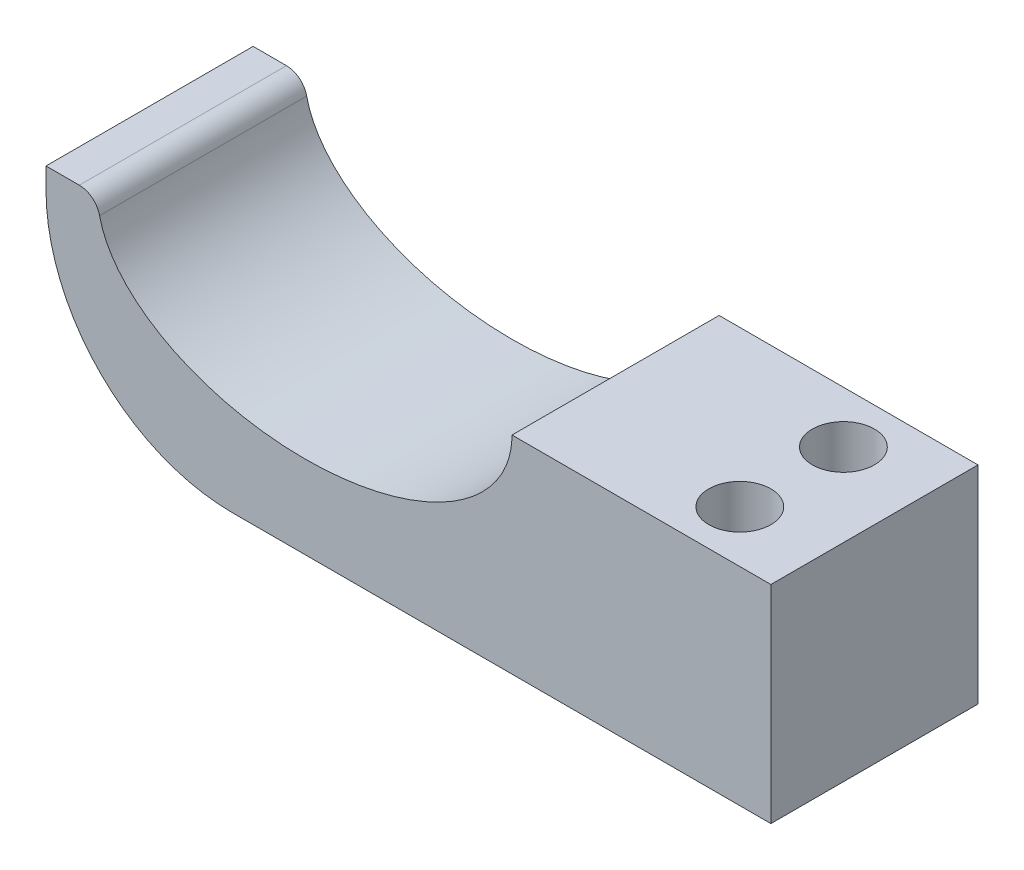
SolidWorks part; units mm, degrees
ref_plane "Front Plane" through (0, 0, 0) normal (0, 0, 1) x (1, 0, 0)
ref_plane "Top Plane" through (0, 0, 0) normal (0, 1, 0) x (1, 0, 0)
ref_plane "Right Plane" through (0, 0, 0) normal (1, 0, 0) x (0, 0, -1)
sketch "Sketch1" plane through (0, 0, 0) normal (0, 1, 0) x (1, 0, 0)
  line L1 (-44.45, 12.7) -> (44.45, 12.7)
  line L2 (-44.45, 12.7) -> (-44.45, -12.7)
  line L3 (-44.45, -12.7) -> (44.45, -12.7)
  line L4 (44.45, 12.7) -> (44.45, -12.7)
  line L5 (-44.45, 12.7) -> (44.45, -12.7) construction
  line L6 (-44.45, -12.7) -> (44.45, 12.7) construction
  point P1 (0, 0)
  dimension "D1" = 88.9
  dimension "D2" = 25.4
extrude "Boss-Extrude1" add sketch "Sketch1" along normal blind 25.4
sketch "Sketch2" plane through (0, 0, 12.7) normal (0, 0, 1) x (1, 0, 0)
  line L0 (-44.45, 25.4) -> (44.45, 25.4) construction
  ellipse E0 centre (-12.7, 25.4) end of major axis (-38.1, 25.4) minor radius 15.24
  dimension "D1" = 6.35
  dimension "D2" = 15.24
  dimension "D3" = 50.8
extrude "Cut-Extrude1" cut sketch "Sketch2" against normal through all
fillet "Fillet1" radius 2.54 1 edges at (-38.1, 25.4, 0)
sketch "Sketch5" plane through (0, 25.4, 0) normal (0, 1, 0) x (1, 0, 0)
  line L0 (34.29, 6.35) -> (34.29, 0) construction
  line L1 (34.29, 0) -> (34.29, -6.35) construction
  line L2 (44.45, -12.7) -> (44.45, 12.7) construction
  circle A0 centre (34.29, 6.35) radius 3.81
  circle A1 centre (34.29, -6.35) radius 3.81
  dimension "D1" = 7.62
  dimension "D2" = 12.7
  dimension "D3" = 10.16
extrude "Cut-Extrude2" cut sketch "Sketch5" against normal through all
fillet "Fillet2" radius 22.86 1 edges at (-44.45, 0, 0)
